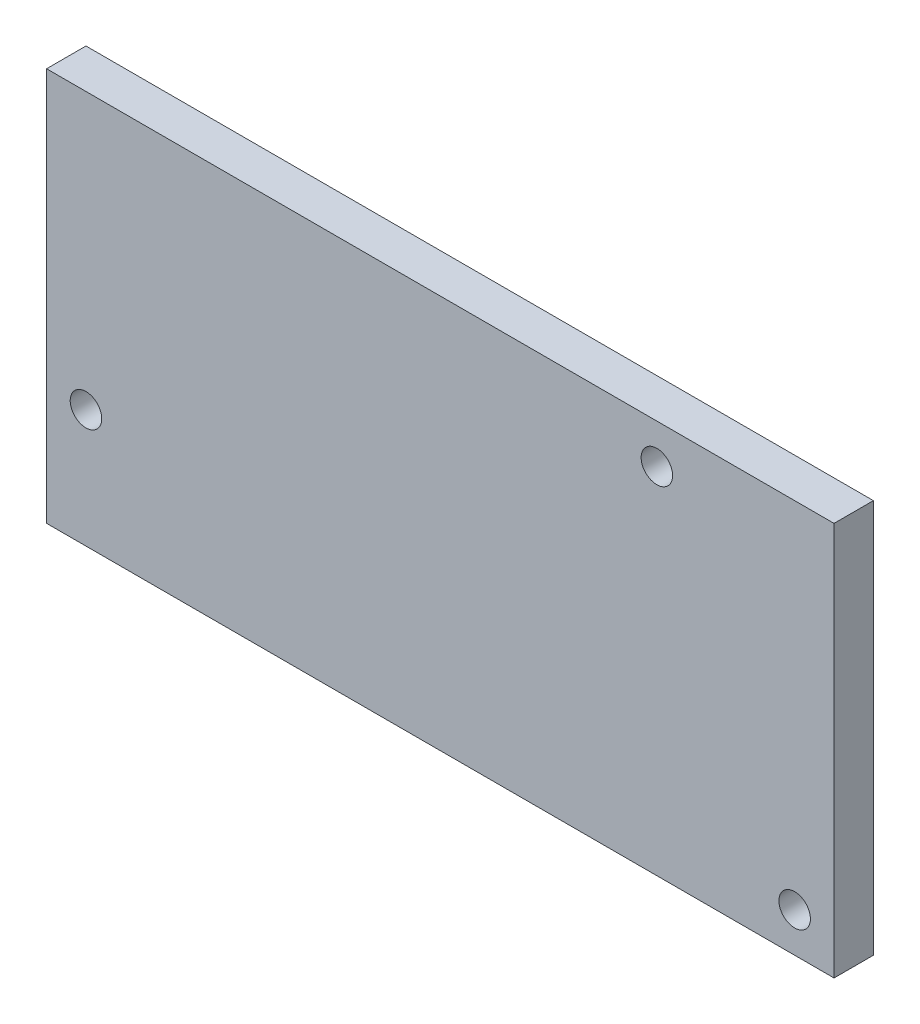
SolidWorks part; units mm, degrees
ref_plane "Front Plane" through (0, 0, 0) normal (0, 0, 1) x (1, 0, 0)
ref_plane "Top Plane" through (0, 0, 0) normal (0, 1, 0) x (1, 0, 0)
ref_plane "Right Plane" through (0, 0, 0) normal (1, 0, 0) x (0, 0, -1)
sketch "Sketch1" plane through (0, 0, 0) normal (0, 0, 1) x (1, 0, 0)
  line L1 (0, 0) -> (200, 0)
  line L2 (0, 0) -> (0, 100)
  line L3 (0, 100) -> (200, 100)
  line L4 (200, 0) -> (200, 100)
  circle A0 centre (10, 30) radius 4
  circle A1 centre (190, 10) radius 4
  circle A2 centre (155, 90) radius 4
  dimension "D3" = 8
  dimension "D8" = 8
  dimension "D1" = 200
  dimension "D2" = 100
  dimension "D4" = 10
  dimension "D5" = 30
  dimension "D6" = 10
  dimension "D7" = 10
  dimension "D9" = 10
  dimension "D10" = 45
extrude "Boss-Extrude1" add sketch "Sketch1" along normal blind 10
